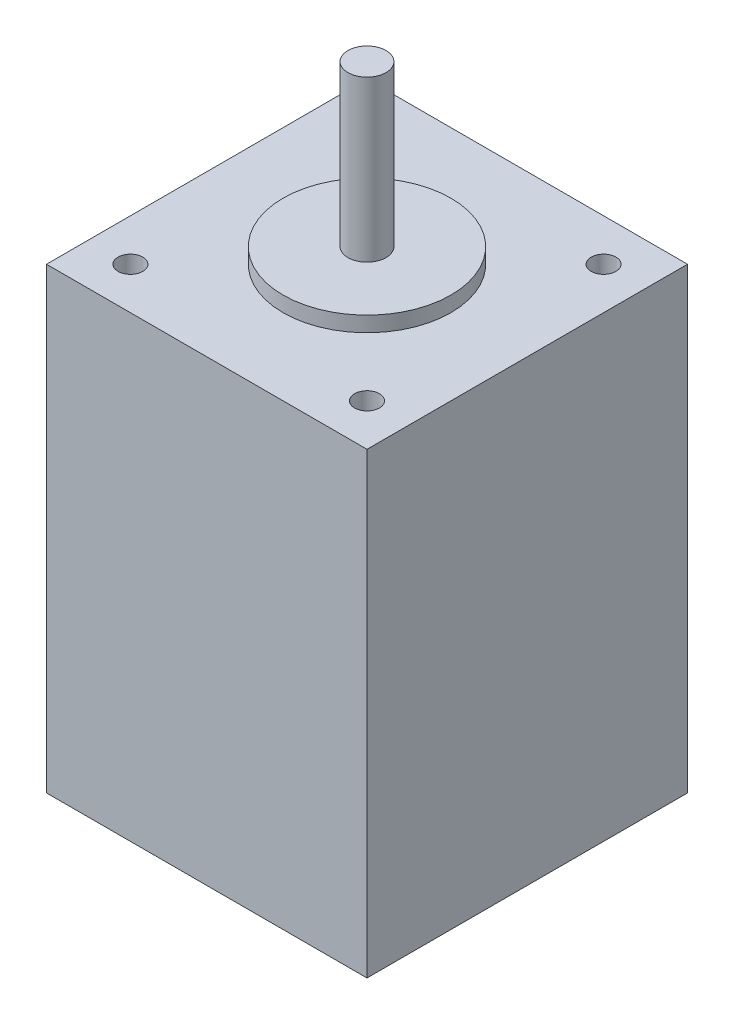
SolidWorks part; units mm, degrees
ref_plane "前视基准面" through (0, 0, 0) normal (0, 0, 1) x (1, 0, 0)
ref_plane "上视基准面" through (0, 0, 0) normal (0, 1, 0) x (1, 0, 0)
ref_plane "右视基准面" through (0, 0, 0) normal (1, 0, 0) x (0, 0, -1)
other "Configuration Table"
sketch "草图1" plane through (0, 0, 0) normal (0, 1, 0) x (1, 0, 0)
  line L1 (0, 0) -> (42, 0)
  line L2 (0, 0) -> (0, 42)
  line L3 (0, 42) -> (42, 42)
  line L4 (42, 0) -> (42, 42)
  dimension "D1" = 42
  dimension "D2" = 42
extrude "凸台-拉伸1" add sketch "草图1" along normal blind 60
sketch "草图2" plane through (0, 60, 0) normal (0, 1, 0) x (1, 0, 0)
  line L0 (42, 0) -> (42, 42) construction
  line L1 (0, 21) -> (42, 21) construction
  line L2 (0, 42) -> (0, 0) construction
  line L3 (21, 42) -> (21, 0) construction
  line L4 (42, 42) -> (0, 42) construction
  line L5 (0, 0) -> (42, 0) construction
  circle A0 centre (21, 21) radius 11
  point P14 (21, 21)
  dimension "D1" = 22
extrude "凸台-拉伸2" add sketch "草图2" along normal blind 2
sketch "草图3" plane through (0, 62, 0) normal (0, 1, 0) x (1, 0, 0)
  circle A0 centre (21, 21) radius 2.5
  dimension "D1" = 5
extrude "凸台-拉伸3" add sketch "草图3" along normal blind 21
sketch "草图4" plane through (0, 60, 0) normal (0, 1, 0) x (1, 0, 0)
  line L0 (42, 0) -> (42, 42) construction
  line L1 (5.5, 36.5) -> (36.5, 36.5) construction
  line L2 (5.5, 36.5) -> (5.5, 5.5) construction
  line L3 (5.5, 5.5) -> (36.5, 5.5) construction
  line L4 (36.5, 36.5) -> (36.5, 5.5) construction
  line L5 (42, 42) -> (0, 42) construction
  circle A0 centre (5.5, 36.5) radius 1.625
  circle A1 centre (36.5, 36.5) radius 1.625
  circle A2 centre (36.5, 5.5) radius 1.625
  circle A3 centre (5.5, 5.5) radius 1.625
  dimension "D5" = 3.25
  dimension "D1" = 31
  dimension "D2" = 31
  dimension "D3" = 5.5
  dimension "D4" = 5.5
extrude "切除-拉伸1" cut sketch "草图4" against normal through all
